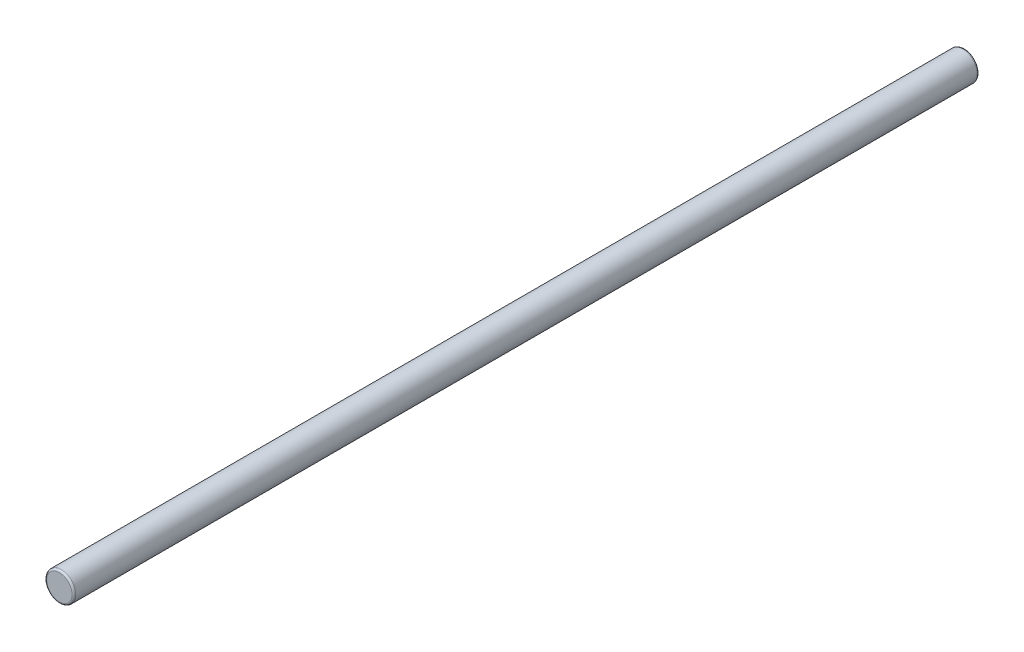
SolidWorks part; units mm, degrees
ref_plane "Plan de face" through (0, 0, 0) normal (0, 0, 1) x (1, 0, 0)
ref_plane "Plan de dessus" through (0, 0, 0) normal (0, 1, 0) x (1, 0, 0)
ref_plane "Plan de droite" through (0, 0, 0) normal (1, 0, 0) x (0, 0, -1)
sketch "Esquisse1" plane through (0, 0, 0) normal (0, 0, 1) x (1, 0, 0)
  circle A0 centre (0, 0) radius 4
  dimension "D1" = 8
extrude "Boss.-Extru.1" add sketch "Esquisse1" along normal blind 250
fillet "Congé1" radius 0.5 2 edges at (4, 0, 250) (4, 0, 0)
